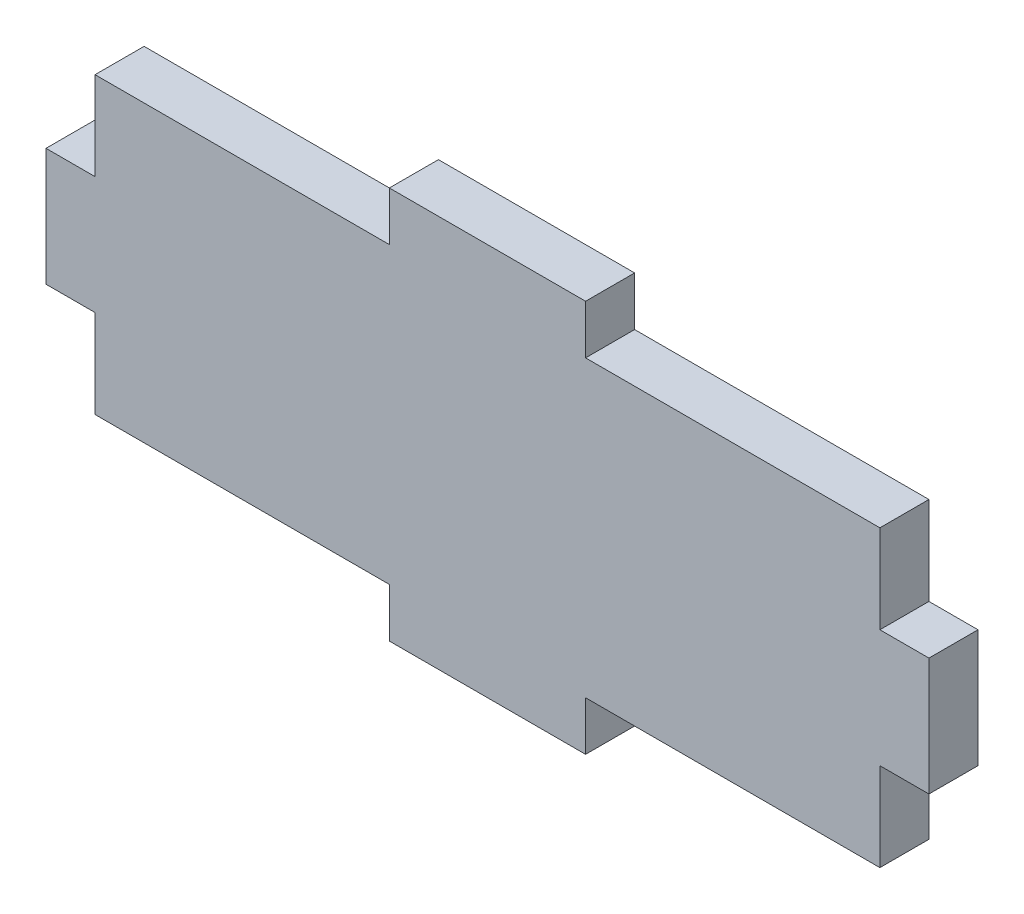
SolidWorks part; units mm, degrees
ref_plane "Front Plane" through (0, 0, 0) normal (0, 0, 1) x (1, 0, 0)
ref_plane "Top Plane" through (0, 0, 0) normal (0, 1, 0) x (1, 0, 0)
ref_plane "Right Plane" through (0, 0, 0) normal (1, 0, 0) x (0, 0, -1)
sketch "Sketch1" plane through (0, 0, 0) normal (0, 0, 1) x (1, 0, 0)
  line L0 (-44.6875, 0) -> (58.2812, 0) construction
  line L1 (-45, -6) -> (-45, 6)
  line L2 (-45, 6) -> (-40, 6)
  line L3 (-40, 6) -> (-40, 15)
  line L4 (-40, 15) -> (-10, 15)
  line L5 (-10, 15) -> (-10, 20)
  line L6 (-10, 20) -> (10, 20)
  line L7 (0, 36.5855) -> (0, -20.4666) construction
  line L8 (10, 15) -> (10, 20)
  line L9 (40, 15) -> (10, 15)
  line L10 (40, 6) -> (40, 15)
  line L11 (45, 6) -> (40, 6)
  line L12 (45, -6) -> (45, 6)
  line L13 (45, -6) -> (40, -6)
  line L14 (40, -6) -> (40, -15)
  line L15 (40, -15) -> (10, -15)
  line L16 (10, -15) -> (10, -20)
  line L17 (-10, -20) -> (10, -20)
  line L18 (-10, -15) -> (-10, -20)
  line L19 (-40, -15) -> (-10, -15)
  line L20 (-40, -6) -> (-40, -15)
  line L21 (-45, -6) -> (-40, -6)
  point P3 (0, -20)
  point P13 (0, 20)
  point P19 (45, 0)
  point P28 (-45, 0)
  dimension "D1" = 5
  dimension "D2" = 20
  dimension "D3" = 12
  dimension "D4" = 80
  dimension "D5" = 30
extrude "Boss-Extrude1" add sketch "Sketch1" along normal blind 5
